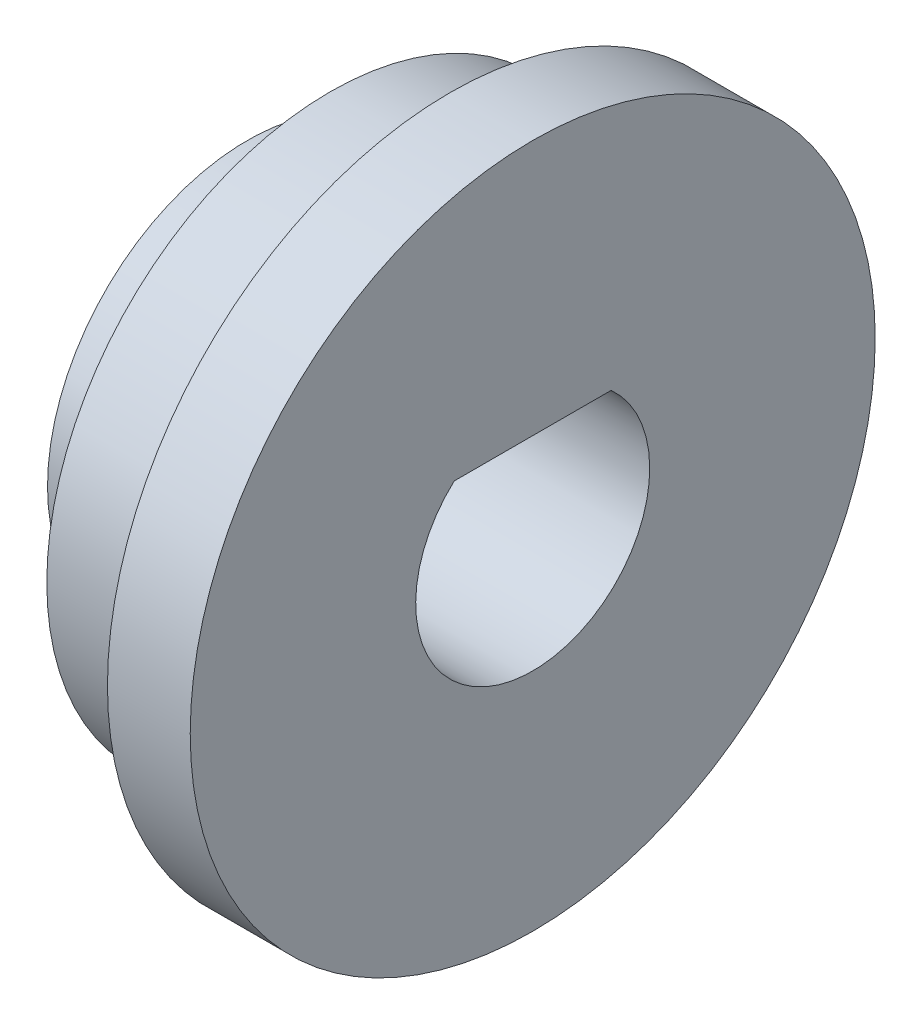
SolidWorks part; units mm, degrees
ref_plane "Ebene vorne" through (0, 0, 0) normal (0, 0, 1) x (1, 0, 0)
ref_plane "Ebene oben" through (0, 0, 0) normal (0, 1, 0) x (1, 0, 0)
ref_plane "Ebene rechts" through (0, 0, 0) normal (1, 0, 0) x (0, 0, -1)
sketch "Skizze1" plane through (0, 0, 0) normal (0, 0, 1) x (1, 0, 0)
  line L0 (0, 0) -> (-16052.284, 0) construction
  line L1 (0, 0) -> (0, 7)
  line L2 (0, 7) -> (2.9, 7)
  line L3 (2.9, 7) -> (2.9, 9.925)
  line L4 (2.9, 9.925) -> (7.1, 9.925)
  line L7 (7.1, 9.925) -> (7.1, 12)
  line L8 (7.1, 12) -> (10, 12)
  line L9 (10, 12) -> (10, 0)
  line L10 (10, 0) -> (0, 0)
  dimension "D1" = 2.9
  dimension "D2" = 24
  dimension "D3" = 4.2
  dimension "D4" = 10
  dimension "D5" = 14
  dimension "D6" = 19.85
revolve "Rotation1" add sketch "Skizze1" angle 360 about L0
sketch "Skizze2" plane through (0, 0, 0) normal (-1, 0, 0) x (0, 0, 1)
  line L0 (-2.75, 3.041) -> (2.75, 3.041)
  arc A0 (-2.75, 3.041) -> (2.75, 3.041) centre (0, 0) ccw
  dimension "D1" = 4.1
  dimension "D2" = 5.5
extrude "Schnitt-Linear austragen1" cut sketch "Skizze2" against normal through all
